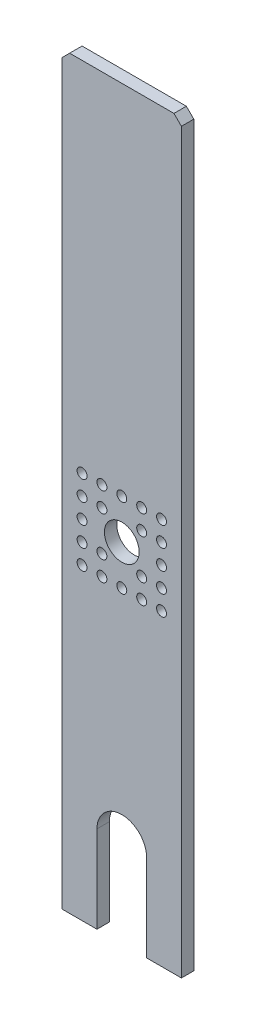
SolidWorks part; units mm, degrees
material "PMMA"
ref_plane "Front Plane" through (0, 0, 0) normal (0, 0, 1) x (1, 0, 0)
ref_plane "Top Plane" through (0, 0, 0) normal (0, 1, 0) x (1, 0, 0)
ref_plane "Right Plane" through (0, 0, 0) normal (1, 0, 0) x (0, 0, -1)
sketch "Sketch1" plane through (0, 0, 0) normal (0, 0, 1) x (1, 0, 0)
  line L0 (0, 0) -> (0, -300)
  line L1 (0, -300) -> (48, -300)
  line L2 (48, -300) -> (48, 0)
  line L3 (48, 0) -> (0, 0)
  line L4 (-41.1176, -160) -> (104.5651, -160) construction
  line L5 (24, 0) -> (24, -275.5734) construction
  line L6 (24, -160) -> (0, -136) construction
  circle A0 centre (24, -160) radius 7
  circle A1 centre (8, -144) radius 2
  circle A2 centre (16, -144) radius 2
  circle A3 centre (24, -144) radius 2
  circle A4 centre (32, -144) radius 2
  circle A5 centre (40, -144) radius 2
  circle A6 centre (16, -152) radius 2
  circle A8 centre (32, -152) radius 2
  circle A9 centre (40, -152) radius 2
  circle A13 centre (40, -160) radius 2
  circle A14 centre (16, -168) radius 2
  circle A16 centre (32, -168) radius 2
  circle A17 centre (40, -168) radius 2
  circle A18 centre (16, -176) radius 2
  circle A19 centre (24, -176) radius 2
  circle A20 centre (32, -176) radius 2
  circle A21 centre (40, -176) radius 2
  circle A22 centre (8, -152) radius 2
  circle A23 centre (8, -160) radius 2
  circle A24 centre (8, -168) radius 2
  circle A25 centre (8, -176) radius 2
  circle A26 centre (16, -160) radius 2 [skipped]
  circle A27 centre (24, -152) radius 2 [skipped]
  circle A28 centre (32, -160) radius 2 [skipped]
  circle A29 centre (24, -168) radius 2 [skipped]
  circle A30 centre (24, -160) radius 2 [skipped]
  dimension "D3" = 14
  dimension "D5" = 4
  dimension "D1" = 48
  dimension "D2" = 300
  dimension "D4" = 45
  dimension "D6" = 16
  dimension "D9" = 160
  dimension "D7" = 5
  dimension "D8" = 5
extrude "Boss-Extrude1" add sketch "Sketch1" along normal blind 5
chamfer "Chamfer1" distance 3 angle 45 2 edges at (0, 0, 2.5) (48, 0, 2.5)
sketch "Sketch2" plane through (0, 0, 5) normal (0, 0, 1) x (1, 0, 0)
  line L0 (24, -300) -> (24, -214.554) construction
  line L1 (0, -300) -> (48, -300) construction
  line L2 (14, -265) -> (14, -300)
  line L3 (14, -300) -> (34, -300)
  line L4 (34, -300) -> (34, -265)
  arc A0 (34, -265) -> (14, -265) centre (24, -265) ccw
  dimension "D1" = 20
  dimension "D2" = 35
extrude "Cut-Extrude1" cut sketch "Sketch2" against normal through all
